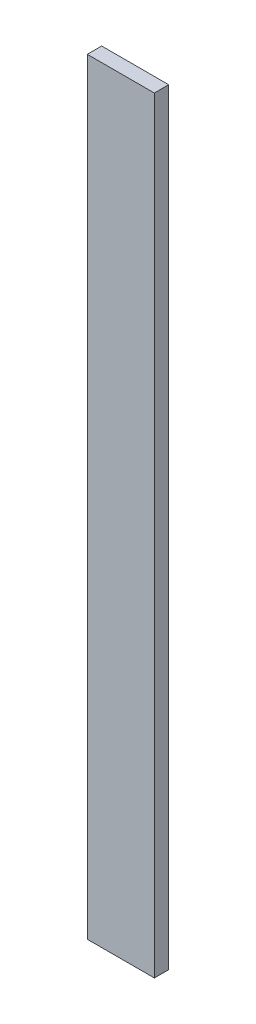
SolidWorks part; units mm, degrees
ref_plane "Front Plane" through (0, 0, 0) normal (0, 0, 1) x (1, 0, 0)
ref_plane "Top Plane" through (0, 0, 0) normal (0, 1, 0) x (1, 0, 0)
ref_plane "Right Plane" through (0, 0, 0) normal (1, 0, 0) x (0, 0, -1)
sketch "Sketch3" plane through (0, 0, 0) normal (0, 0, 1) x (1, 0, 0)
  line L1 (0, 0) -> (-70, 0)
  line L2 (0, 0) -> (0, -800)
  line L3 (0, -800) -> (-70, -800)
  line L4 (-70, 0) -> (-70, -800)
  dimension "D1" = 70
  dimension "D2" = 800
extrude "Boss-Extrude1" add sketch "Sketch3" along normal blind 15 contours L2 L3 L4 L1
sketch "Sketch4" plane through (0, 0, 0) normal (0, 0, -1) x (-1, 0, 0)
  line L0 (0, 0) -> (70, 0) construction
  line L1 (70, 0) -> (70, -800) construction
  circle A0 centre (35, -30) radius 10
  circle A7 centre (35, -150) radius 10
  circle A8 centre (35, -270) radius 10
  circle A9 centre (35, -390) radius 10
  circle A10 centre (35, -510) radius 10
  circle A11 centre (35, -630) radius 10
  circle A12 centre (35, -750) radius 10
  point P6 (0, 0)
  dimension "D1" = 20
  dimension "D5" = 120
  dimension "D2" = 30
  dimension "D3" = 35
  dimension "D4" = 7
extrude "Cut-Extrude1" cut sketch "Sketch4" against normal blind 8 contours A0 | A7 | A8 | A9 | A10 | A11 | A12
